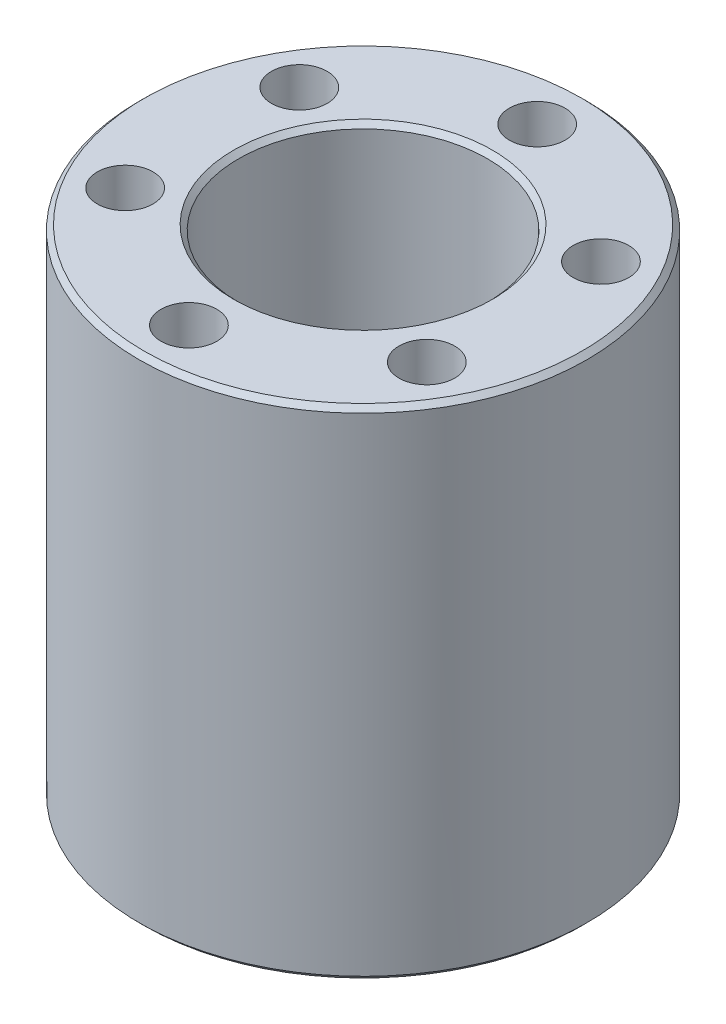
SolidWorks part; units mm, degrees
ref_plane "Ebene vorne" through (0, 0, 0) normal (0, 0, 1) x (1, 0, 0)
ref_plane "Ebene oben" through (0, 0, 0) normal (0, 1, 0) x (1, 0, 0)
ref_plane "Ebene rechts" through (0, 0, 0) normal (1, 0, 0) x (0, 0, -1)
sketch "Sketch2" plane through (0, 0, 0) normal (0, 0, 1) x (1, 0, 0)
  line L0 (0, 0) -> (0, 50) construction
  line L1 (12.5, 0) -> (12.5, 25)
  line L2 (12.5, 25) -> (22.5, 25)
  line L3 (22.5, 25) -> (22.5, 0)
  line L4 (22.5, 0) -> (12.5, 0)
  dimension "D1" = 50
  dimension "D2" = 45
  dimension "D3" = 25
  dimension "D4" = 25
revolve "Revolve1" add sketch "Sketch2" angle 360 about L0
hole_wizard "Ø5.6 (5.6) Diameter Hole1" positions "Sketch3" profile "Sketch5" hole size "Ø5.6" standard "DIN"
sketch "Sketch3" plane through (0, 25, 0) normal (0, 1, 0) x (1, 0, 0)
  line L0 (0, -12.5) -> (0, -22.5) construction
  circle A0 centre (0, 0) radius 12.5 construction
  circle A1 centre (0, 0) radius 22.5 construction
  point P9 (0, -17.5)
  point P17 (-15.1554, -8.75)
  point P18 (-15.1554, 8.75)
  point P19 (0, 17.5)
  point P20 (15.1554, 8.75)
  point P21 (15.1554, -8.75)
  dimension "D1" = 6
sketch "Sketch5" plane through (15.1554, 25, 8.75) normal (1, 0, 0) x (0, 0, 1)
  line L0 (0, 0) -> (0, 9.6824)
  line L1 (0, 9.6824) -> (2.8, 8)
  line L2 (2.8, 8) -> (2.8, 0)
  line L5 (2.8, 0) -> (0, 0)
  line L10 (0, 9.6824) -> (-2.8, 8) construction
  line L11 (0, -6.35) -> (0, 107.95) construction
  dimension "Hole Dia." = 5.6
  dimension "Hole Depth" = 8
  dimension "Drill Angle" = 118
mirror "Mirror1" about plane through (0, 0, 0) normal (0, 1, 0) of "Revolve1", "Ø5.6 (5.6) Diameter Hole1"
chamfer "0,5mm Chamfer1" distance 0.5 angle 45 4 edges at (0, -25, -12.5) (0, -25, -22.5) (0, 25, -12.5) (0, 25, -22.5)
